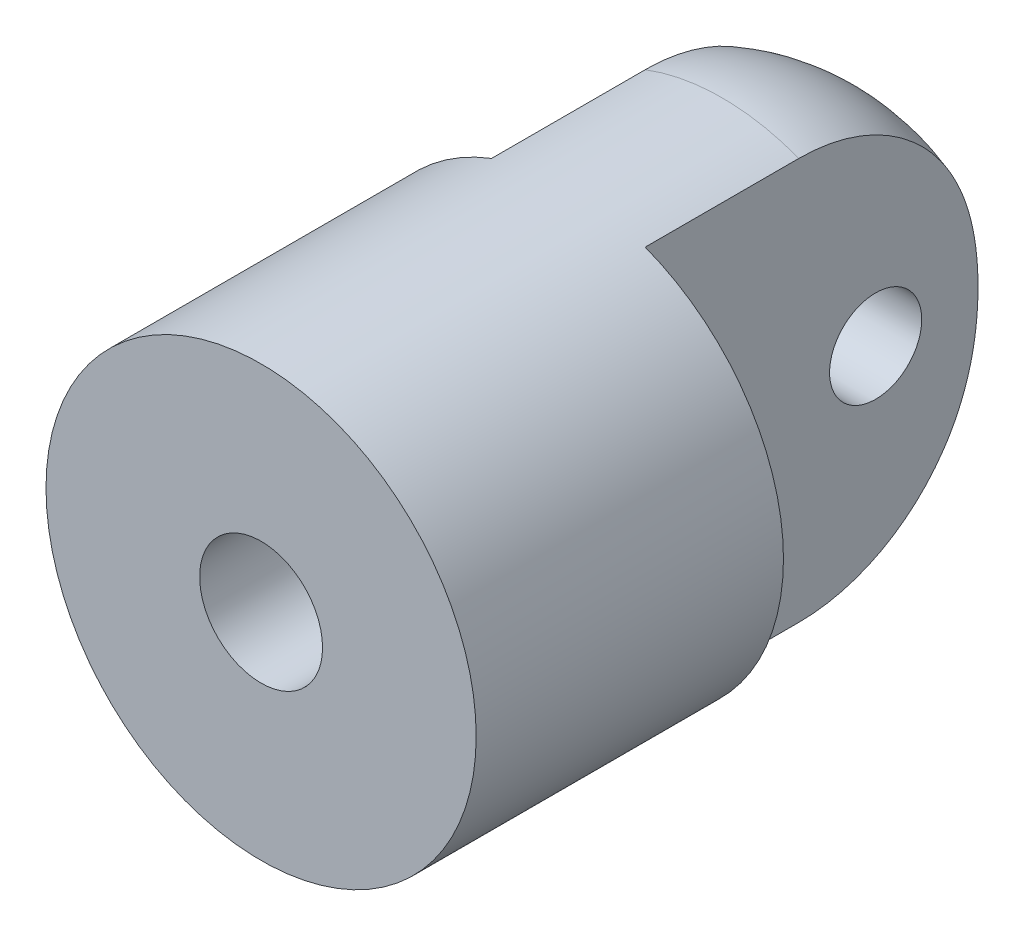
SolidWorks part; units mm, degrees
ref_plane "Ön Düzlem" through (0, 0, 0) normal (0, 0, 1) x (1, 0, 0)
ref_plane "Üst Düzlem" through (0, 0, 0) normal (0, 1, 0) x (1, 0, 0)
ref_plane "Sağ Düzlem" through (0, 0, 0) normal (1, 0, 0) x (0, 0, -1)
sketch "Sketch1" plane through (0, 0, 0) normal (1, 0, 0) x (0, 0, -1)
  line L0 (0, 0) -> (0, 14)
  line L1 (0, 14) -> (30, 14)
  line L3 (-8.7538, 0) -> (49.0602, 0) construction
  line L4 (0, 0) -> (41.8969, 0)
  arc A1 (30, 14) -> (41.8969, 0) centre (30, 1.9451) cw
  dimension "D1" = 14
  dimension "D2" = 30
revolve "Revolve1" add sketch "Sketch1" angle 360 about L3
sketch "Sketch2" plane through (0, 0, 0) normal (0, 0, 1) x (1, 0, 0)
  circle A0 centre (0, 0) radius 4
extrude "Cut-Extrude1" cut sketch "Sketch2" against normal blind 30
sketch "Sketch3" plane through (0, 0, 0) normal (0, 1, 0) x (1, 0, 0)
  line L1 (-24.1261, 52.2535) -> (-5, 52.2535)
  line L2 (-24.1261, 52.2535) -> (-24.1261, 20)
  line L3 (-24.1261, 20) -> (-5, 20)
  line L4 (-5, 52.2535) -> (-5, 20)
  line L5 (-14, 0) -> (14, 0) construction
  line L6 (5, 45.8162) -> (19.7259, 45.8162)
  line L7 (5, 45.8162) -> (5, 20)
  line L8 (5, 20) -> (19.7259, 20)
  line L9 (19.7259, 45.8162) -> (19.7259, 20)
  dimension "D1" = 5
  dimension "D2" = 5
  dimension "D3" = 20
  dimension "D4" = 14.7259
  dimension "D5" = 20
extrude "Cut-Extrude2" cut sketch "Sketch3" against normal mid plane 30
sketch "Sketch4" plane through (5, 0, 0) normal (1, 0, 0) x (0, 0, -1)
  circle A0 centre (35, 0) radius 3
extrude "Cut-Extrude3" cut sketch "Sketch4" against normal blind 30
